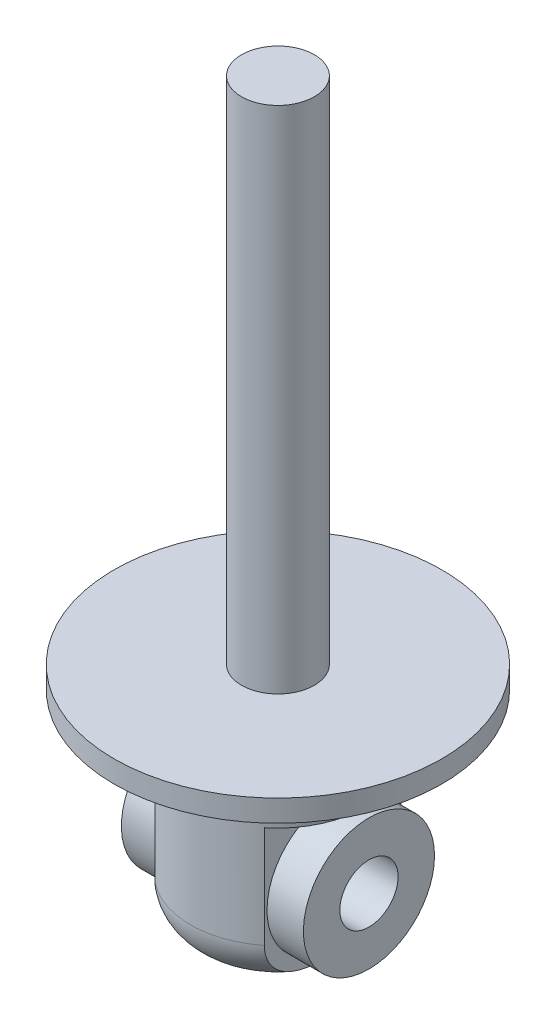
SolidWorks part; units mm, degrees
material "1060 Alloy"
ref_plane "Front Plane" through (0, 0, 0) normal (0, 0, 1) x (1, 0, 0)
ref_plane "Top Plane" through (0, 0, 0) normal (0, 1, 0) x (1, 0, 0)
ref_plane "Right Plane" through (0, 0, 0) normal (1, 0, 0) x (0, 0, -1)
sketch "Sketch2" plane through (0, 0, 0) normal (0, 1, 0) x (1, 0, 0)
  circle A0 centre (0, 0) radius 22.5
  dimension "D1" = 45
extrude "Boss-Extrude1" add sketch "Sketch2" along normal blind 3
sketch "Sketch4" plane through (0, 3, 0) normal (0, 1, 0) x (1, 0, 0)
  circle A0 centre (0, 0) radius 5
  dimension "D1" = 10
extrude "Boss-Extrude2" add sketch "Sketch4" along normal blind 70
sketch "Sketch5" plane through (0, 0, 0) normal (0, -1, 0) x (1, 0, 0)
  circle A0 centre (0, 0) radius 12
  dimension "D1" = 24
extrude "Boss-Extrude3" add sketch "Sketch5" along normal blind 28
fillet "Fillet1" radius 6 1 edges at (0, -28, -12)
sketch "Sketch6" plane through (0, 0, 0) normal (0, 0, 1) x (1, 0, 0)
  line L0 (0, 0) -> (0, -28) construction
  line L2 (7.5, -28) -> (26.5, -28)
  line L3 (26.5, -28) -> (26.5, -8)
  line L4 (26.5, -8) -> (7.5, -8)
  line L5 (7.5, -8) -> (7.5, -28)
  line L6 (-12, 0) -> (12, 0) construction
  line L7 (-6, -28) -> (6, -28) construction
  line L8 (-7.5, -8) -> (-7.5, -28)
  line L9 (-26.5, -8) -> (-7.5, -8)
  line L10 (-26.5, -28) -> (-26.5, -8)
  line L11 (-7.5, -28) -> (-26.5, -28)
  dimension "D1" = 15
  dimension "D2" = 20
  dimension "D3" = 19
extrude "Cut-Extrude1" cut sketch "Sketch6" against normal through all both and the other way through all
sketch "Sketch7" plane through (7.5, 0, 0) normal (1, 0, 0) x (0, 0, -1)
  line L0 (0, 0) -> (0, -28) construction
  line L1 (-6, -28) -> (6, -28) construction
  circle A0 centre (0, -18) radius 4
  dimension "D1" = 8
  dimension "D2" = 10
extrude "Cut-Extrude2" cut sketch "Sketch7" against normal through all
sketch "Sketch8" plane through (0, 0, 0) normal (1, 0, 0) x (0, 0, -1)
  circle A0 centre (0, -18) radius 9
  circle A1 centre (0, -18) radius 4 construction
  circle A2 centre (0, -18) radius 4
  dimension "D1" = 18
extrude "Boss-Extrude4" add sketch "Sketch8" along normal mid plane 25
